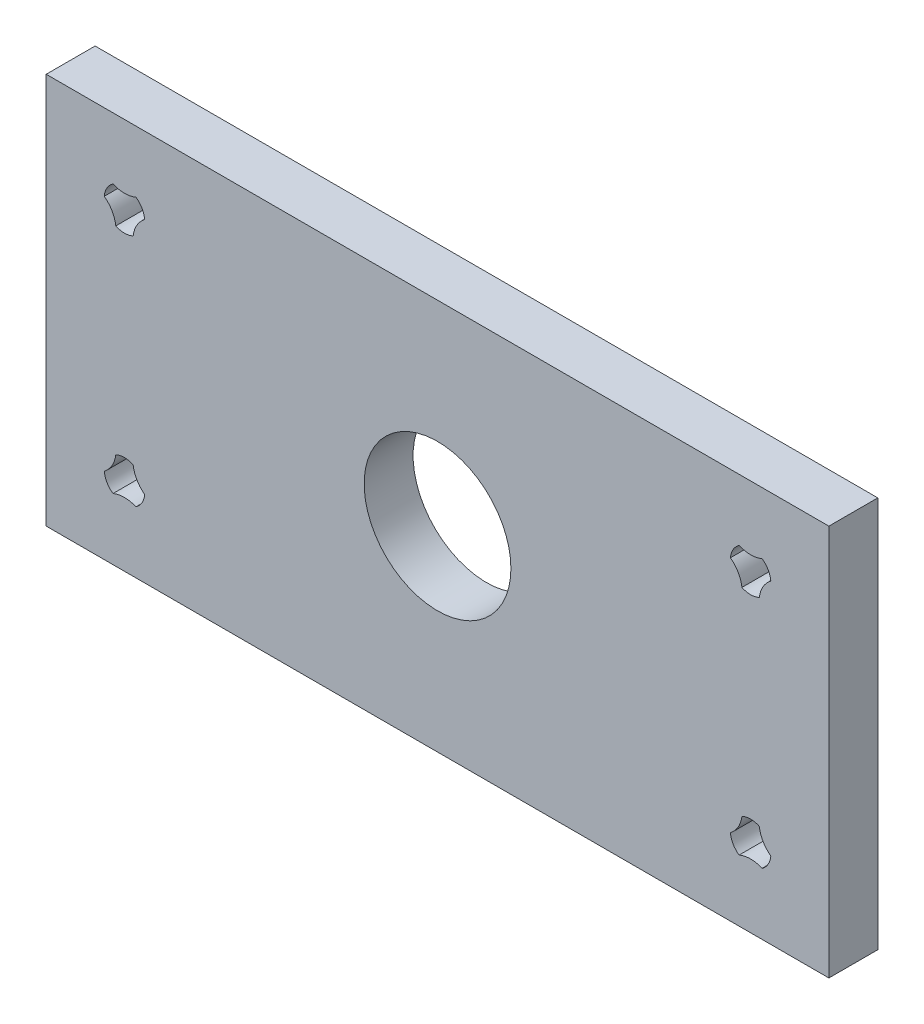
SolidWorks part; units mm, degrees
ref_plane "Plan de face" through (0, 0, 0) normal (0, 0, 1) x (1, 0, 0)
ref_plane "Plan de dessus" through (0, 0, 0) normal (0, 1, 0) x (1, 0, 0)
ref_plane "Plan de droite" through (0, 0, 0) normal (1, 0, 0) x (0, 0, -1)
sketch "Esquisse1" plane through (0, 0, 0) normal (0, 0, 1) x (1, 0, 0)
  line L0 (0, -23.3772) -> (0, -18.3772) construction
  line L1 (-40, -23.3772) -> (40, -23.3772)
  line L2 (-40, -23.3772) -> (-40, 16.6228)
  line L3 (-40, 16.6228) -> (40, 16.6228)
  line L4 (40, -23.3772) -> (40, 16.6228)
  line L5 (-40, -23.3772) -> (40, 16.6228) construction
  line L6 (-40, 16.6228) -> (40, -23.3772) construction
  line L7 (-32, 16.6228) -> (-32, 8.6228) construction
  line L8 (-32, 8.6228) -> (-40, 8.6228) construction
  line L9 (0, -3.3772) -> (4.7279, -3.3772) construction
  circle A0 centre (-32, 8.6228) radius 2.0696
  arc A1 (-33.1758, 10.3261) -> (-30.8242, 10.3261) centre (-32, 13.0861) ccw
  arc A2 (-29.9371, 8.7895) -> (-31.1128, 6.753) centre (-28.1347, 6.3912) ccw
  arc A3 (-32.8872, 6.753) -> (-34.0629, 8.7895) centre (-35.8653, 6.3912) ccw
  arc A5 (32.8872, 6.753) -> (34.0629, 8.7895) centre (35.8653, 6.3912) cw
  arc A6 (29.9371, 8.7895) -> (31.1128, 6.753) centre (28.1347, 6.3912) cw
  arc A7 (33.1758, 10.3261) -> (30.8242, 10.3261) centre (32, 13.0861) cw
  circle A9 centre (32, 8.6228) radius 2.0696
  circle A10 centre (32, -15.3772) radius 2.0696
  arc A11 (33.1758, -17.0804) -> (30.8242, -17.0804) centre (32, -19.8404) ccw
  circle A12 centre (0, -3.3772) radius 7.5
  arc A13 (29.9371, -15.5438) -> (31.1128, -13.5073) centre (28.1347, -13.1456) ccw
  arc A14 (32.8872, -13.5073) -> (34.0629, -15.5438) centre (35.8653, -13.1456) ccw
  arc A15 (-32.8872, -13.5073) -> (-34.0629, -15.5438) centre (-35.8653, -13.1456) cw
  arc A16 (-29.9371, -15.5438) -> (-31.1128, -13.5073) centre (-28.1347, -13.1456) cw
  arc A17 (-33.1758, -17.0804) -> (-30.8242, -17.0804) centre (-32, -19.8404) cw
  circle A18 centre (-32, -15.3772) radius 2.0696
  point P0 (0, -3.3772)
  dimension "D3" = 15
  dimension "D1" = 80
  dimension "D2" = 5
  dimension "D4" = 40
  dimension "D5" = 8
  dimension "D6" = 3
extrude "Boss.-Extru.1" add sketch "Esquisse1" along normal blind 5 contours L1 L4 L3 L2 A12 A10 A0 A9 A18 | A0 A3 | A0 A1 | A0 A2 | A18 A16 | A18 A15 | A18 A17 | A9 A7 | A9 A6 | A9 A5 | A10 A14 | A10 A13 | A10 A11
